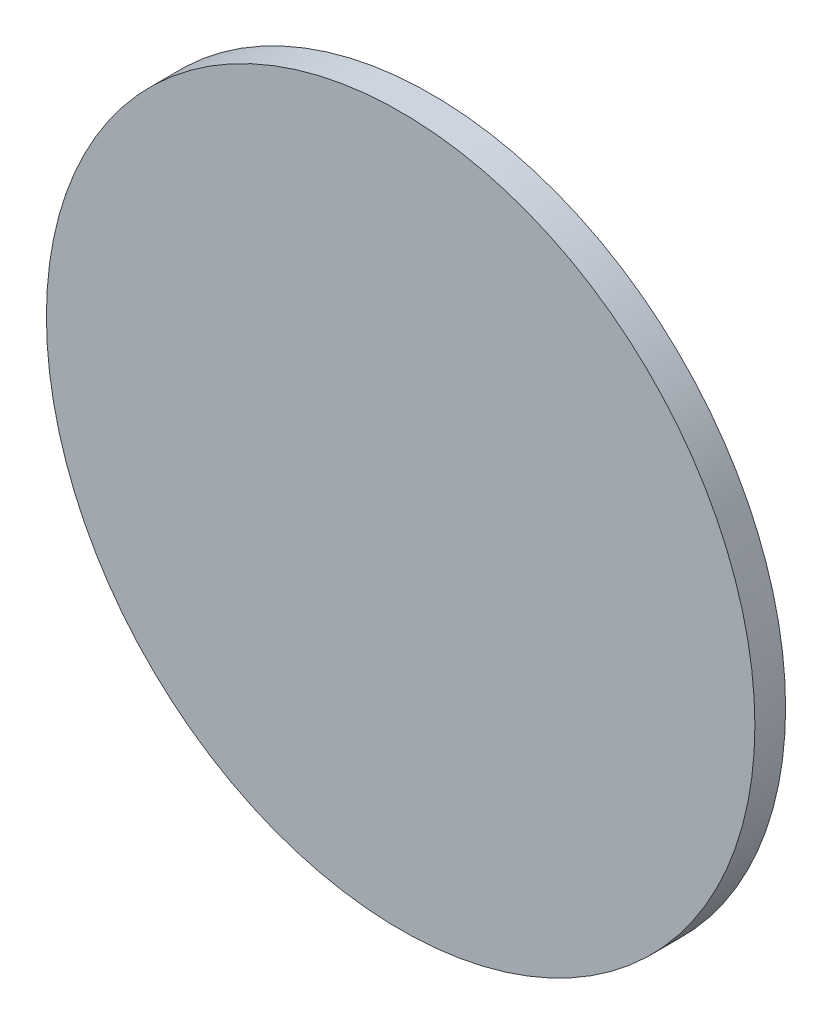
SolidWorks part; units mm, degrees
ref_plane "Front" through (0, 0, 0) normal (0, 0, 1) x (1, 0, 0)
ref_plane "Top" through (0, 0, 0) normal (0, 1, 0) x (1, 0, 0)
ref_plane "Right" through (0, 0, 0) normal (1, 0, 0) x (0, 0, -1)
sketch "Sketch1" plane through (0, 0, 0) normal (0, 0, 1) x (1, 0, 0)
  circle A0 centre (0, 0) radius 23.0708
extrude "Extrude1" add sketch "Sketch1" along normal blind 2
